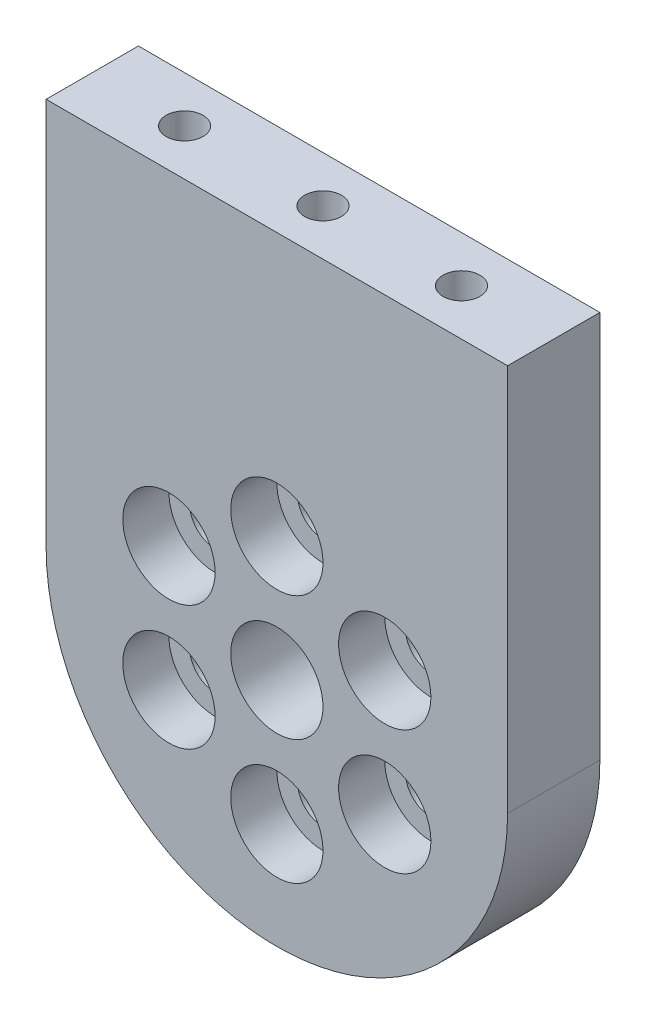
SolidWorks part; units mm, degrees
material "1060 합금"
ref_plane "정면" through (0, 0, 0) normal (0, 0, 1) x (1, 0, 0)
ref_plane "윗면" through (0, 0, 0) normal (0, 1, 0) x (1, 0, 0)
ref_plane "우측면" through (0, 0, 0) normal (1, 0, 0) x (0, 0, -1)
sketch "스케치1" plane through (0, 0, 0) normal (0, 0, 1) x (1, 0, 0)
  line L0 (0, 0) -> (0, 101.3519) construction
  line L1 (25, 0) -> (25, 42)
  line L2 (-25, 0) -> (-25, 42)
  line L3 (-25, 42) -> (25, 42)
  arc A0 (-25, 0) -> (25, 0) centre (0, 0) ccw
  circle A1 centre (0, 0) radius 5
  circle A3 centre (0, 0) radius 13.5 construction
  circle A4 centre (0, -13.5) radius 2.75
  circle A5 centre (-11.6913, -6.75) radius 2.75
  circle A6 centre (-11.6913, 6.75) radius 2.75
  circle A7 centre (0, 13.5) radius 2.75
  circle A8 centre (11.6913, 6.75) radius 2.75
  circle A9 centre (11.6913, -6.75) radius 2.75
  point P24 (0, 0)
  dimension "D1" = 50
  dimension "D2" = 42
  dimension "D5" = 27
  dimension "D6" = 5.5
  dimension "D7" = 6
extrude "보스-돌출1" add sketch "스케치1" along normal blind 10
sketch "스케치2" plane through (0, 42, 0) normal (0, 1, 0) x (1, 0, 0)
  line L0 (-25, -5) -> (25, -5) construction
  line L1 (-25, -10) -> (-25, 0) construction
  line L2 (25, -10) -> (25, 0) construction
  circle A0 centre (0, -5) radius 2
  circle A1 centre (15, -5) radius 2
  circle A2 centre (-15, -5) radius 2
  dimension "D1" = 4
  dimension "D2" = 4
  dimension "D3" = 4
  dimension "D4" = 15
  dimension "D5" = 15
extrude "컷-돌출1" cut sketch "스케치2" against normal blind 20
sketch "스케치4" plane through (0, 0, 10) normal (0, 0, 1) x (1, 0, 0)
  circle A0 centre (0, 13.5) radius 5
  circle A1 centre (11.6913, 6.75) radius 5
  circle A2 centre (11.6913, -6.75) radius 5
  circle A3 centre (0, -13.5) radius 5
  circle A4 centre (-11.6913, -6.75) radius 5
  circle A5 centre (-11.6913, 6.75) radius 5
  dimension "D1" = 10
extrude "컷-돌출3" cut sketch "스케치4" against normal blind 5
